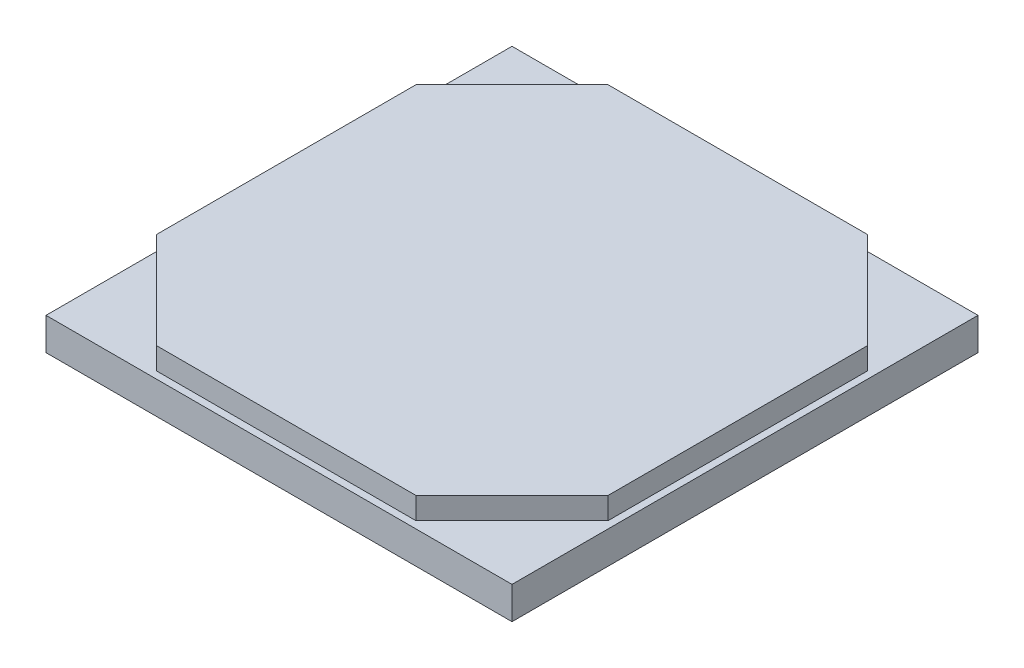
SolidWorks part; units mm, degrees
ref_plane "Спереди" through (0, 0, 0) normal (0, 0, 1) x (1, 0, 0)
ref_plane "Сверху" through (0, 0, 0) normal (0, 1, 0) x (1, 0, 0)
ref_plane "Справа" through (0, 0, 0) normal (1, 0, 0) x (0, 0, -1)
sketch "Эскиз1" plane through (0, 0, 0) normal (1, 0, 0) x (0, 0, -1)
  line L1 (-7.2974, 0.8536) -> (2.5026, 0.8536)
  line L2 (-7.2974, 0.8536) -> (-7.2974, 0.1736)
  line L3 (-7.2974, 0.1736) -> (2.5026, 0.1736)
  line L4 (2.5026, 0.8536) -> (2.5026, 0.1736)
  point P4 (17.4352, 3.2117)
  point P5 (18.8335, 2.0756)
  dimension "D1" = 9.8
  dimension "D2" = 0.68
extrude "Бобышка-Вытянуть1" add sketch "Эскиз1" along normal blind 9.8
sketch "Эскиз3" plane through (0, 0.8536, 0) normal (0, 1, 0) x (1, 0, 0)
  line L0 (9.8, 2.5026) -> (0, 2.5026) construction
  line L1 (0, 2.5026) -> (9.8, 2.5026)
  line L2 (0, 2.5026) -> (0, -7.2974)
  line L3 (0, -7.2974) -> (9.8, -7.2974)
  line L4 (9.8, 2.5026) -> (9.8, -7.2974)
  line L5 (0, 2.5026) -> (0, -7.2974) construction
  line L6 (2.32, 2.5026) -> (0, 0.1826)
  line L7 (7.48, 2.5026) -> (9.8, 0.1826)
  line L8 (9.8, -4.9774) -> (7.48, -7.2974)
  line L9 (0, -4.9774) -> (2.32, -7.2974)
  line L10 (2.17, 2.3526) -> (7.63, 2.3526)
  line L11 (9.65, 0.3326) -> (9.65, -5.1274)
  line L12 (2.17, -7.1474) -> (7.63, -7.1474)
  line L13 (0.15, 0.3326) -> (0.15, -5.1274)
  dimension "D1" = 2.32
  dimension "D2" = 2.32
  dimension "D3" = 2.32
  dimension "D4" = 2.32
  dimension "D5" = 2.32
  dimension "D6" = 2.32
  dimension "D7" = 0.15
  dimension "D8" = 0.15
  dimension "D9" = 0.15
  dimension "D10" = 0.15
  dimension "D11" = 2.32
  dimension "D12" = 2.32
extrude "Бобышка-Вытянуть2" add sketch "Эскиз3" along normal blind 0.46 contours L2 L9 L3 L8 L4 L7 L1 L6
